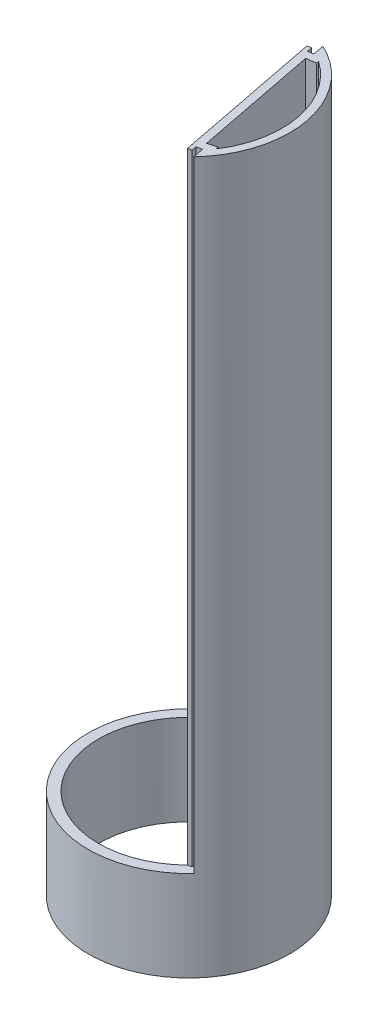
SolidWorks part; units mm, degrees
ref_plane "Front Plane" through (0, 0, 0) normal (0, 0, 1) x (1, 0, 0)
ref_plane "Top Plane" through (0, 0, 0) normal (0, 1, 0) x (1, 0, 0)
ref_plane "Right Plane" through (0, 0, 0) normal (1, 0, 0) x (0, 0, -1)
sketch "Sketch12" plane through (0, 0, 0) normal (0, 1, 0) x (1, 0, 0)
  line L0 (8.6347, 15.5184) -> (8.2084, 17.6882)
  line L1 (8.6347, 15.5184) -> (7.568, 15.3643)
  line L2 (7.568, 15.3643) -> (7.3752, 16.3458)
  line L3 (7.3752, 16.3458) -> (6.6214, 16.1774)
  line L4 (12.7902, -11.4418) -> (13.8366, -11.1839)
  line L5 (13.8366, -11.1839) -> (14.2509, -13.3102)
  line L6 (12.7902, -11.4418) -> (12.9718, -12.3819)
  line L7 (12.9718, -12.3819) -> (12.218, -12.5008)
  line L8 (6.6214, 16.1774) -> (12.218, -12.5008)
  line L18 (10.4107, 14.2594) -> (10.3139, 14.752)
  line L19 (15.0077, -9.3505) -> (15.0959, -9.8037)
  line L20 (13.2176, -9.7916) -> (15.0077, -9.3505)
  line L23 (8.5757, 13.9943) -> (13.2176, -9.7916)
  line L26 (10.4107, 14.2594) -> (8.5757, 13.9943)
  line L27 (10.4107, 14.2594) -> (10.3139, 14.7521)
  line L28 (15.0077, -9.3506) -> (15.0959, -9.8037)
  line L29 (13.2176, -9.7916) -> (15.0077, -9.3506)
  line L32 (8.5757, 13.9943) -> (13.2176, -9.7916)
  line L35 (10.4107, 14.2594) -> (8.5757, 13.9943)
  arc A3 (14.2509, -13.3102) -> (8.2084, 17.6882) centre (0, 0) ccw
  arc A5 (15.0959, -9.8037) -> (10.3139, 14.752) centre (0, 0) ccw
  arc A6 (15.0959, -9.8037) -> (10.3139, 14.7521) centre (0, 0) ccw
  point P1 (0, 0)
  point P3 (0, 0)
  point P6 (0, 0)
  point P9 (0, 0)
  point P11 (0, 0)
  point P13 (0, 0)
  point P15 (0, 0)
  point P16 (0, 0)
  dimension "D1" = 19.5
  dimension "D2" = 18
  dimension "D3" = 2.1663
  dimension "D4" = 0.7538
  dimension "D5" = 9.5974
  dimension "D6" = 2.1698
  dimension "D7" = 11.0974
  dimension "D8" = 1.835
  dimension "D9" = 1.7901
extrude "Boss-Extrude1" add sketch "Sketch12" along normal blind 120 contours L5 A3 L0 L1 L2 L3 L8 L7 L6 L4 A5 L19 L20 L23 L26 L18
sketch "Sketch28" plane through (0, 0, 0) normal (0, -1, 0) x (1, 0, 0)
  line L5 (10.4107, -14.2594) -> (10.3139, -14.7521)
  line L6 (8.5757, -13.9943) -> (10.4107, -14.2594)
  line L7 (13.2176, 9.7916) -> (8.5757, -13.9943)
  line L8 (15.0077, 9.3505) -> (13.2176, 9.7916)
  line L9 (15.0959, 9.8037) -> (15.0077, 9.3505)
  line L10 (10.4107, -14.2594) -> (10.3139, -14.7521)
  line L11 (8.5757, -13.9943) -> (10.4107, -14.2594)
  line L12 (13.2176, 9.7916) -> (8.5757, -13.9943)
  line L13 (15.0077, 9.3505) -> (13.2176, 9.7916)
  line L14 (15.0959, 9.8037) -> (15.0077, 9.3505)
  arc A1 (10.3139, -14.7521) -> (15.0959, 9.8037) centre (0, 0) ccw
  arc A2 (10.3139, -14.7521) -> (15.0959, 9.8037) centre (0, 0) ccw
  dimension "D1" = 0
extrude "Boss-Extrude3" add sketch "Sketch28" along normal mid plane 15
sketch "Sketch26" plane through (0, 0, 0) normal (0, -1, 0) x (1, 0, 0)
  circle A0 centre (0, 0) radius 19.5
  circle A1 centre (0, 0) radius 17.5
  dimension "D1" = 39
  dimension "D2" = 35
extrude "Boss-Extrude2" add sketch "Sketch26" along normal blind 17.5
